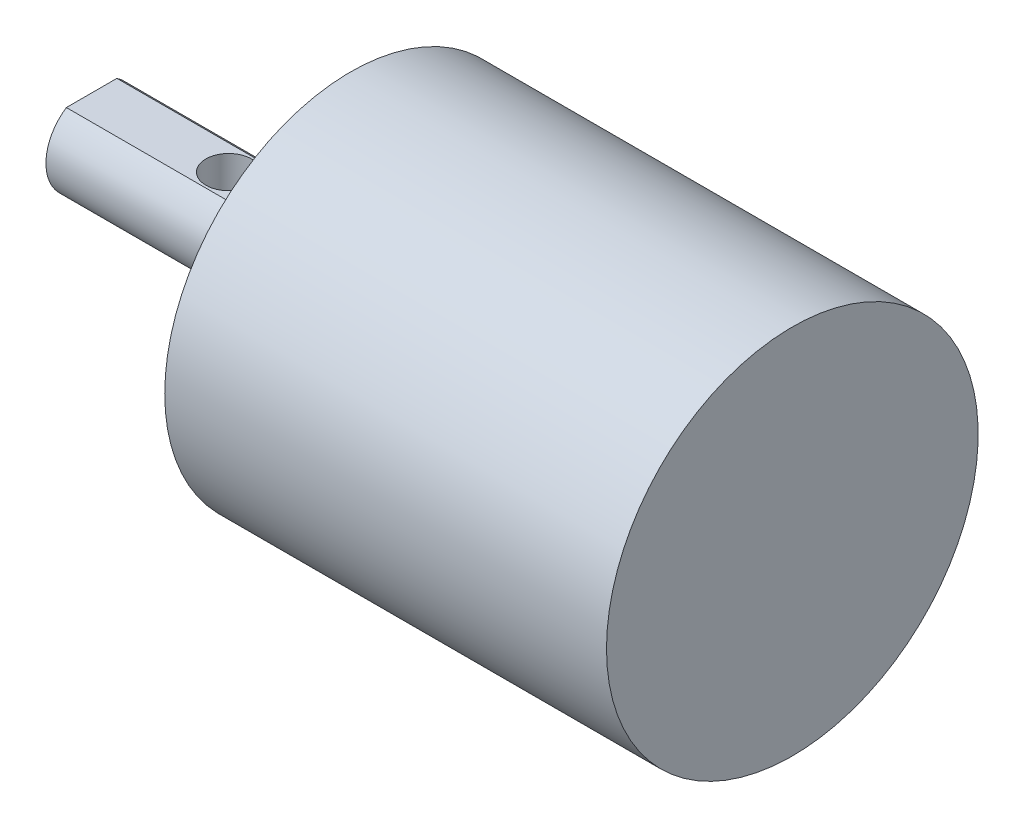
SolidWorks part; units mm, degrees
ref_plane "前视基准面" through (0, 0, 0) normal (0, 0, 1) x (1, 0, 0)
ref_plane "上视基准面" through (0, 0, 0) normal (0, 1, 0) x (1, 0, 0)
ref_plane "右视基准面" through (0, 0, 0) normal (1, 0, 0) x (0, 0, -1)
sketch "草图1" plane through (0, 0, 0) normal (0, 1, 0) x (1, 0, 0)
  line L0 (0, 0) -> (-29, 0)
  line L1 (-29, 0) -> (-29, 5.7)
  line L2 (-29, 5.7) -> (-31.6, 5.7)
  line L3 (-31.6, 5.7) -> (-31.6, 9.2)
  line L4 (-31.6, 9.2) -> (-46, 9.2)
  line L5 (-46, 9.2) -> (-46, 12.2)
  line L6 (-46, 12.2) -> (0, 12.2)
  line L7 (0, 12.2) -> (0, 0)
  dimension "D1" = 29
  dimension "D2" = 5.7
  dimension "D3" = 2.6
  dimension "D4" = 3.5
  dimension "D5" = 14.4
  dimension "D6" = 3
revolve "旋转1" add sketch "草图1" angle 360 about L6
sketch "草图2" plane through (-46, 0, 0) normal (-1, 0, 0) x (0, 0, 1)
  point P0 (-12.2, 0)
sketch "草图9" plane through (-46, 0, 0) normal (-1, 0, 0) x (0, 0, 1)
  line L0 (-12.2, 2.5) -> (-10.5417, 2.5)
  line L1 (-12.2, 2.5) -> (-13.8583, 2.5)
  line L2 (-13.8583, 2.5) -> (-12.2, 2.5)
  circle A0 centre (-12.2, 0) radius 3 construction
  arc A1 (-10.5417, 2.5) -> (-13.8583, 2.5) centre (-12.2, 0) ccw
extrude "切除-拉伸3" cut sketch "草图9" against normal blind 11.5 contours L1 A1 L0
hole_wizard "M3 螺纹孔1" positions "草图10" profile "草图11" tap size "M3" standard "GB"
sketch "草图10" plane through (-46, 0, 0) normal (-1, 0, 0) x (0, 0, 1)
  point P0 (-12.2, 0)
sketch "草图11" plane through (-46, 0, -12.2) normal (0, 1, 0) x (0, 0, 1)
  line L0 (0, 0) -> (0, 6.2511)
  line L1 (0, 6.2511) -> (1.25, 5.5)
  line L2 (1.25, 5.5) -> (1.25, 0)
  line L5 (1.25, 0) -> (0, 0)
  line L10 (0, 6.2511) -> (-1.25, 5.5) construction
  line L11 (0, -6.35) -> (0, 107.95) construction
  dimension "螺纹孔钻头直径" = 2.5
  dimension "螺纹孔钻头深度" = 5.5
  dimension "导头角度" = 118
cosmetic thread "孔螺蚊线2" parameters "D1"=5.5, "D2"=3
sketch "草图12" plane through (0, 2.5, 0) normal (0, 1, 0) x (1, 0, 0)
  line L0 (-46, 10.5417) -> (-46, 13.8583) construction
  circle A0 centre (-37, 12.2) radius 1.5
  point P0 (-37, 12.2)
  dimension "D1" = 3
  dimension "D2" = 9
extrude "切除-拉伸4" cut sketch "草图12" against normal blind 11.5 contours A0
sketch "草图13" plane through (-29, 0, 0) normal (-1, 0, 0) x (0, 0, 1)
  circle A1 centre (-12.2, 9.5) radius 1.5
  circle A2 centre (-3.9728, -4.75) radius 1.5
  circle A3 centre (-20.4272, -4.75) radius 1.5
  point P11 (-12.2, 0)
  dimension "D2" = 3
  dimension "D3" = 3
hole_wizard "M3 螺纹孔2" positions "草图14" profile "草图15" tap size "M3" standard "GB"
sketch "草图14" plane through (-29, 0, 0) normal (-1, 0, 0) x (0, 0, 1)
  point P2 (-12.2, 9.5)
  point P5 (-20.4272, -4.75)
  point P8 (-3.9728, -4.75)
sketch "草图15" plane through (-29, 9.5, -12.2) normal (0, 1, 0) x (0, 0, 1)
  line L0 (0, 0) -> (0, 4.7511)
  line L1 (0, 4.7511) -> (1.25, 4)
  line L2 (1.25, 4) -> (1.25, 0)
  line L5 (1.25, 0) -> (0, 0)
  line L10 (0, 4.7511) -> (-1.25, 4) construction
  line L11 (0, -6.35) -> (0, 107.95) construction
  dimension "螺纹孔钻头直径" = 2.5
  dimension "螺纹孔钻头深度" = 4
  dimension "导头角度" = 118
cosmetic thread "孔螺蚊线3" parameters "D1"=4, "D2"=3
cosmetic thread "孔螺蚊线4" parameters "D1"=4, "D2"=3
cosmetic thread "孔螺蚊线5" parameters "D1"=4, "D2"=3
sketch "草图16" plane through (-31.6, 0, 0) normal (-1, 0, 0) x (0, 0, 1)
  line L0 (-9.6019, -1.5) -> (-12.2, -6)
  line L1 (-18.0095, -1.5) -> (-14.6921, 1.6702)
  arc A0 (-12.2, -6) -> (-18.0095, -1.5) centre (-12.2, 0) ccw
  arc A1 (-13.8583, 2.5) -> (-10.5417, 2.5) centre (-12.2, 0) ccw construction
  arc A2 (-14.6921, 1.6702) -> (-9.6019, -1.5) centre (-12.2, 0) cw
  dimension "D1" = 12
extrude "凸台-拉伸1" add sketch "草图16" along normal blind 0.5 contours A0 L1 A2 L0
sketch "草图4" plane through (-46, 0, 0) normal (-1, 0, 0) x (0, 0, 1)
  circle A0 centre (-12.2, 0) radius 1.5
  point P0 (-12.2, 0)
  dimension "D1" = 3
